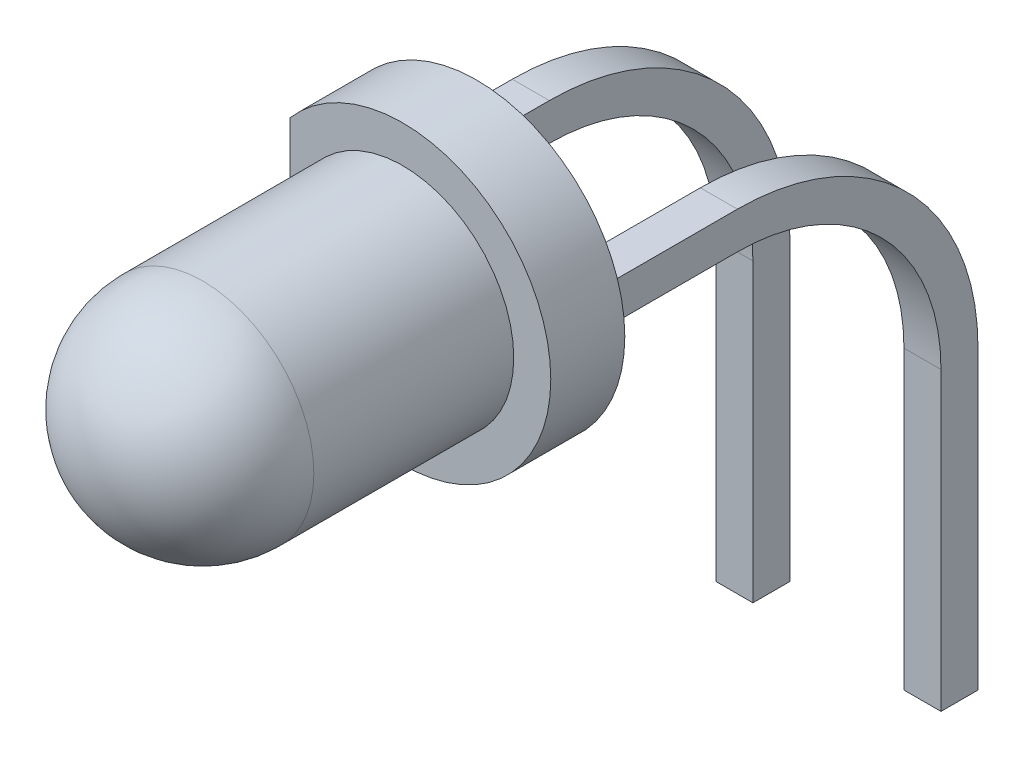
SolidWorks part; units mm, degrees
ref_plane "Спереди" through (0, 0, 0) normal (0, 0, 1) x (1, 0, 0)
ref_plane "Сверху" through (0, 0, 0) normal (0, 1, 0) x (1, 0, 0)
ref_plane "Справа" through (0, 0, 0) normal (1, 0, 0) x (0, 0, -1)
sketch "Эскиз2" plane through (0, 0, 0) normal (0, 0, 1) x (1, 0, 0)
  line L0 (0, 0) -> (0, 3) construction
  line L1 (-1.52, 4.2998) -> (-1.52, 1.7002)
  arc A0 (-1.52, 1.7002) -> (-1.52, 4.2998) centre (0, 3) ccw
  dimension "D1" = 4
  dimension "D2" = 3
  dimension "D3" = 1.52
sketch "Эскиз3" plane through (0, 0, 0) normal (1, 0, 0) x (0, -1, 0)
  line L0 (3.0294, -6) -> (-5.8021, -6) construction
  line L1 (-3, -13.2968) -> (-3, -0.2074) construction
  line L2 (-4.5, -6) -> (-4.5, -8.7)
  line L3 (-4.5, -6) -> (-3, -6)
  line L4 (-3, -10.2) -> (-3, -6)
  arc A1 (-4.5, -8.7) -> (-3, -10.2) centre (-3, -8.7) ccw
  point P11 (-3, -10.2)
  dimension "D1" = 6
  dimension "D2" = 3
  dimension "D3" = 1.5
  dimension "D4" = 4.2
extrude "Бобышка-Вытянуть2" add sketch "Эскиз2" along normal blind 1 from offset 5
revolve "Повернуть1" add sketch "Эскиз3" angle 360 about L1
sketch "Эскиз4" plane through (0, 0, 5) normal (0, 0, 1) x (1, 0, 0)
  line L0 (1.83, 3) -> (-3.4254, 3) construction
  line L1 (0, 0.0576) -> (0, 5.1378) construction
  line L2 (-1.52, 2.75) -> (-1.02, 2.75)
  line L3 (1.52, 2.75) -> (1.02, 2.75)
  line L4 (1.52, 2.75) -> (1.52, 3.25)
  line L5 (1.52, 3.25) -> (1.02, 3.25)
  line L6 (1.02, 2.75) -> (1.02, 3.25)
  line L7 (1.52, 2.75) -> (1.02, 3.25) construction
  line L8 (1.52, 3.25) -> (1.02, 2.75) construction
  line L9 (-1.02, 2.75) -> (-1.02, 3.25)
  line L10 (-1.52, 2.75) -> (-1.52, 3.25)
  line L11 (-1.52, 3.25) -> (-1.02, 3.25)
  point P0 (0, 0)
  point P6 (1.27, 3)
  dimension "D1" = 3
  dimension "D2" = 1.27
  dimension "D3" = 0.5
  dimension "D4" = 1.52
sketch "Эскиз5" plane through (0, 0, 0) normal (1, 0, 0) x (0, 0, -1)
  line L0 (-5, 3) -> (-3, 3)
  line L1 (0, 0) -> (0, -4)
  arc A0 (-3, 3) -> (0, 0) centre (-3, 0) cw
  point P0 (0, 0)
  dimension "D1" = 3
  dimension "D2" = 4
sweep "По траектории2" add profiles "Эскиз4" path "Эскиз5"
